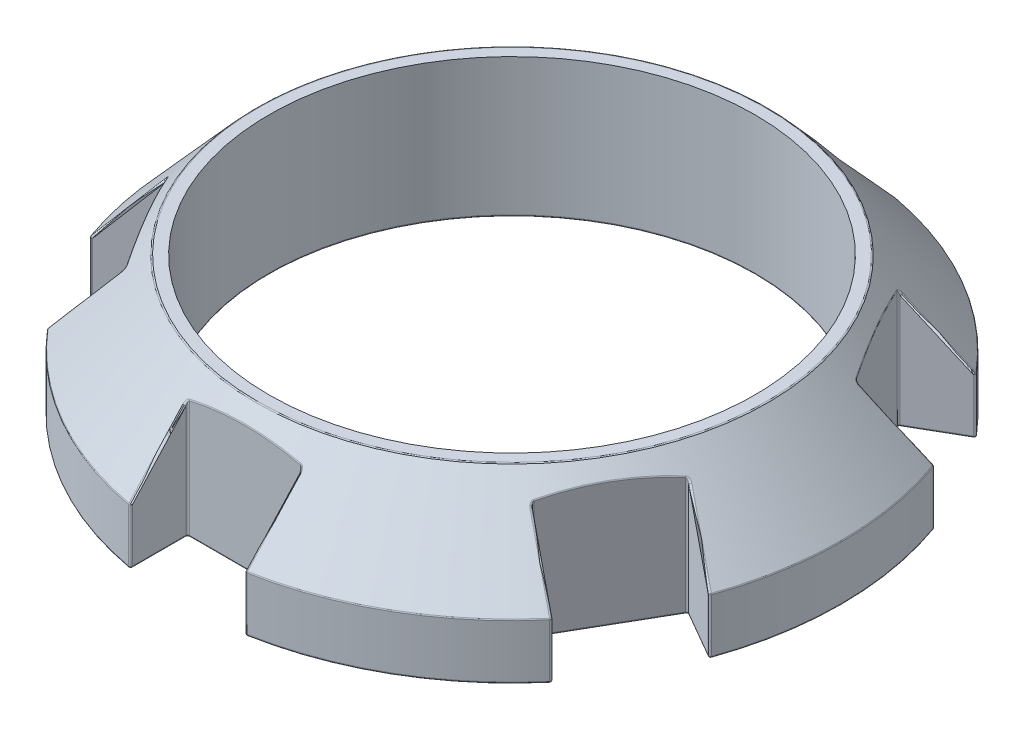
SolidWorks part; units mm, degrees
ref_plane "Front" through (0, 0, 0) normal (0, 0, 1) x (1, 0, 0)
ref_plane "Top" through (0, 0, 0) normal (0, 1, 0) x (1, 0, 0)
ref_plane "Right" through (0, 0, 0) normal (1, 0, 0) x (0, 0, -1)
sketch "Sketch1" plane through (0, 0, 0) normal (0, 1, 0) x (1, 0, 0)
  circle A0 centre (0, 0) radius 7
  circle A1 centre (0, 0) radius 9.5
  dimension "D1" = 19
  dimension "D2" = 14
extrude "Boss-Extrude1" add sketch "Sketch1" along normal blind 4
sketch "Sketch4" plane through (0, 0, 0) normal (1, 0, 0) x (0, 0, -1)
  line L0 (7.35, 4) -> (9.5, 1.6)
  line L1 (9.5, 4) -> (-9.5, 4) construction
  line L2 (9.5, 0) -> (9.5, 4) construction
  line L3 (9.5, 1.6) -> (9.5, 4)
  line L4 (9.5, 4) -> (7.35, 4)
  line L6 (-9.5, 0) -> (9.5, 0) construction
  dimension "D1" = 7.35
  dimension "D2" = 1.6
revolve "Cut-Revolve1" cut sketch "Sketch4" angle 360 about axis through (0, 4, 0) along (0, -1, 0)
sketch "Sketch5" plane through (0, 0, 0) normal (0, -1, 0) x (1, 0, 0)
  line L0 (0, 0) -> (0, 7.7) construction
  line L1 (-1.65, 9.5) -> (1.65, 9.5)
  line L2 (-1.65, 9.5) -> (-1.65, 7.7)
  line L3 (-1.65, 7.7) -> (1.65, 7.7)
  line L4 (1.65, 9.5) -> (1.65, 7.7)
  circle A0 centre (0, 0) radius 9.5 construction
  dimension "D1" = 3.3
  dimension "D2" = 7.7
extrude "Cut-Extrude1" cut sketch "Sketch5" against normal through all
pattern_circular "CirPattern1" count 6 over 360 about axis through (0, 0, 0) along (0, 1, 0) of "Cut-Extrude1"
fillet "Fillet1" radius 0.05 74 edges at (-7.4934, 1.7071, -2.4211) (-5.8434, 1.7071, -5.2789) (-1.65, 1.7071, -7.7) (1.65, 1.7071, -7.7) (-5.8434, 1.7071, 5.2789) (-7.4934, 1.7071, 2.4211) (-6.299, 3.5698, -4.4898) (-7.0378, 3.5698, 3.2102) (-8.9272, 0.8, 3.2489) (-8.9272, 0.8, -3.2489) (-9.5, 1.6, 0) (-7.2772, 0.8, -6.1067) (-1.65, 0.8, -9.3556) (-4.75, 1.6, -8.2272) (1.65, 0.8, -9.3556) (7.2772, 0.8, -6.1067) (4.75, 1.6, -8.2272) (-1.65, 0.8, 9.3556) (-7.2772, 0.8, 6.1067) (-4.75, 1.6, 8.2272) (0, 4, 7.35) (5.8434, 1.7071, -5.2789) (7.4934, 1.7071, -2.4211) (7.0378, 3.5698, -3.2102) (7.4934, 1.7071, 2.4211) (5.8434, 1.7071, 5.2789) (1.65, 1.7071, 7.7) (-1.65, 1.7071, 7.7) (0, 0, 7) (8.2103, 0, 2.835) (8.2103, 0, -2.835) (6.6684, 0, -3.85) (6.5603, 0, -5.6928) (4.75, 0, -8.2272) (1.65, 0, -8.5278) (0, 0, -7.7) (-1.65, 0, -8.5278) (-4.75, 0, -8.2272) (-6.5603, 0, -5.6928) (-6.6684, 0, -3.85) (-8.2103, 0, -2.835) (-9.5, 0, 0) (-8.2103, 0, 2.835) (-6.6684, 0, 3.85) (-6.5603, 0, 5.6928) (-4.75, 0, 8.2272) (-1.65, 0, 8.5278) (0, 0, 7.7) (1.65, 0, 8.5278) (6.5603, 0, 5.6928) (6.6684, 0, 3.85) (6.299, 3.5698, 4.4898) (8.9272, 0.8, -3.2489) (9.5, 0, 0) (8.9272, 0.8, 3.2489) (9.5, 1.6, 0) (1.65, 0.8, 9.3556) (4.75, 1.6, 8.2272) (7.2772, 0.8, 6.1067) (4.75, 0, 8.2272)
